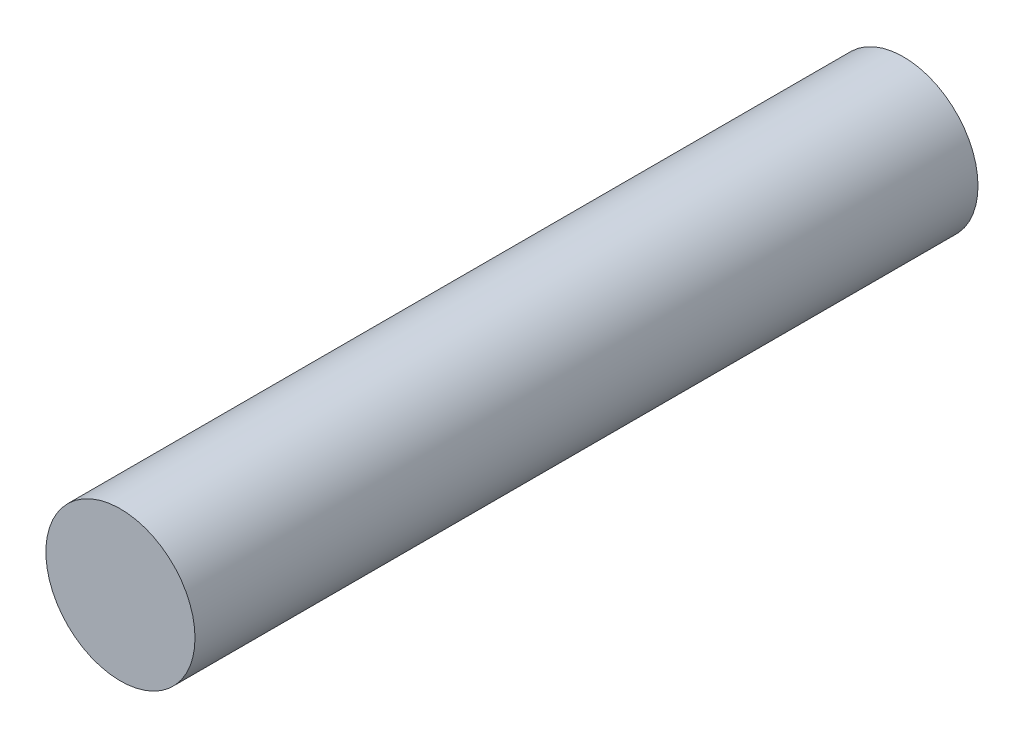
SolidWorks part; units mm, degrees
ref_plane "Front Plane" through (0, 0, 0) normal (0, 0, 1) x (1, 0, 0)
ref_plane "Top Plane" through (0, 0, 0) normal (0, 1, 0) x (1, 0, 0)
ref_plane "Right Plane" through (0, 0, 0) normal (1, 0, 0) x (0, 0, -1)
sketch "Sketch1" plane through (0, 0, 0) normal (0, 0, 1) x (1, 0, 0)
  circle A0 centre (0, 0) radius 2.125
extrude "Boss-Extrude1" add sketch "Sketch1" along normal blind 21
sketch "Sketch3" plane through (0, 0, 21) normal (0, 0, 1) x (1, 0, 0)
  circle A0 centre (0, 0) radius 2
  circle A1 centre (0, 0) radius 2.125
extrude "Cut-Extrude1" cut sketch "Sketch3" against normal blind 28
